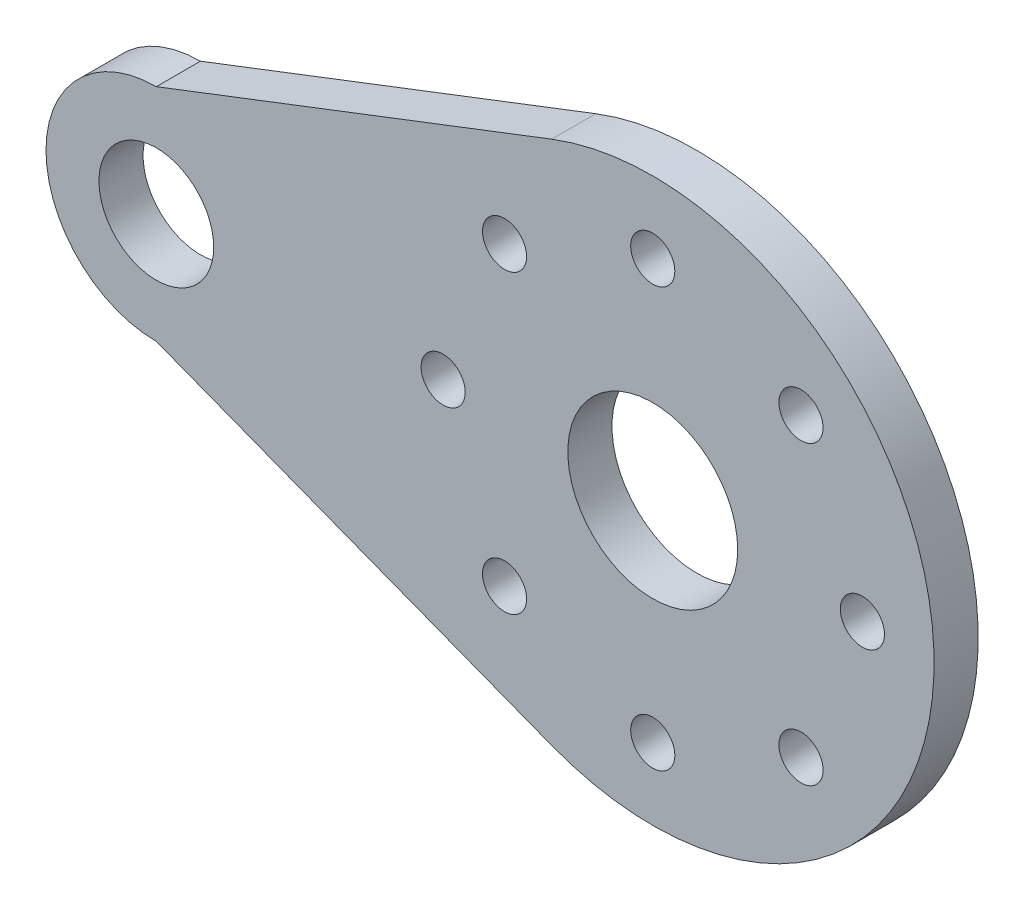
SolidWorks part; units mm, degrees
ref_plane "前视基准面" through (0, 0, 0) normal (0, 0, 1) x (1, 0, 0)
ref_plane "上视基准面" through (0, 0, 0) normal (0, 1, 0) x (1, 0, 0)
ref_plane "右视基准面" through (0, 0, 0) normal (1, 0, 0) x (0, 0, -1)
sketch "草图1" plane through (0, 0, 0) normal (0, 0, 1) x (1, 0, 0)
  line L0 (140.4648, -16.6383) -> (95.4648, -16.6383) construction
  line L1 (95.4648, -26.6383) -> (131.3031, -40.4356)
  line L2 (95.4648, -6.6383) -> (131.3031, 7.1591)
  circle A0 centre (140.4648, -16.6383) radius 7.7
  circle A1 centre (140.4648, -35.6383) radius 2
  circle A2 centre (127.0297, -30.0733) radius 2
  circle A3 centre (121.4648, -16.6383) radius 2
  circle A4 centre (127.0297, -3.2032) radius 2
  circle A5 centre (140.4648, -16.6383) radius 19 construction
  circle A6 centre (140.4648, 2.3617) radius 2
  circle A7 centre (153.8998, -3.2032) radius 2
  circle A8 centre (159.4648, -16.6383) radius 2
  circle A9 centre (153.8998, -30.0733) radius 2
  circle A10 centre (140.4648, -16.6383) radius 25.5 construction
  circle A11 centre (95.4648, -16.6383) radius 10 construction
  circle A12 centre (95.4648, -16.6383) radius 5.2
  arc A13 (95.4648, -26.6383) -> (95.4648, -6.6383) centre (95.4648, -16.6383) cw
  arc A14 (131.3031, 7.1591) -> (131.3031, -40.4356) centre (140.4648, -16.6383) cw
  dimension "D1" = 45
  dimension "D2" = 4
  dimension "D3" = 38
  dimension "D4" = 10.4
  dimension "D5" = 15.4
extrude "凸台-拉伸1" add sketch "草图1" along normal blind 4 contours L1 A14 L2 A13
